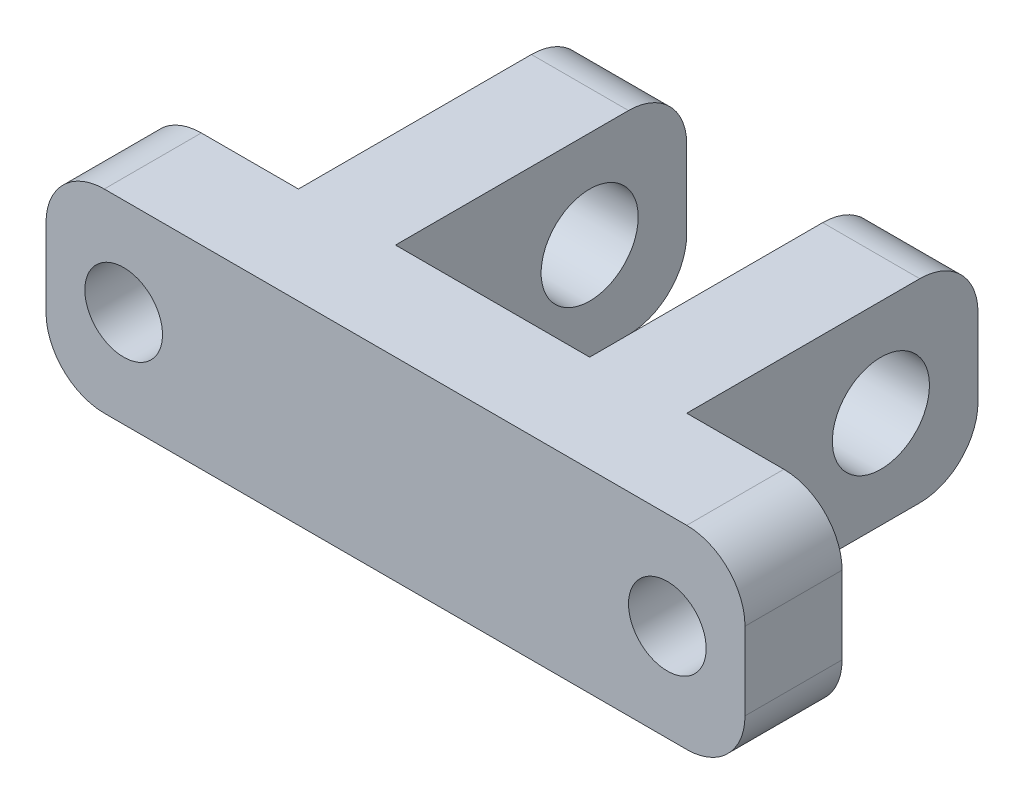
SolidWorks part; units mm, degrees
ref_plane "Front Plane" through (0, 0, 0) normal (0, 0, 1) x (1, 0, 0)
ref_plane "Top Plane" through (0, 0, 0) normal (0, 1, 0) x (1, 0, 0)
ref_plane "Right Plane" through (0, 0, 0) normal (1, 0, 0) x (0, 0, -1)
sketch "Sketch1" plane through (0, 0, 0) normal (0, 1, 0) x (1, 0, 0)
  line L0 (-18, 0) -> (18, 0)
  line L1 (18, 0) -> (18, 5)
  line L2 (18, 5) -> (10, 5)
  line L3 (10, 5) -> (10, 20)
  line L4 (10, 20) -> (5, 20)
  line L5 (5, 20) -> (5, 5)
  line L6 (5, 5) -> (-5, 5)
  line L7 (-5, 5) -> (-5, 20)
  line L8 (-5, 20) -> (-10, 20)
  line L9 (-10, 20) -> (-10, 5)
  line L10 (-10, 5) -> (-18, 5)
  line L11 (-18, 5) -> (-18, 0)
  point P4 (0, 0)
  point P13 (0, 5)
  dimension "D1" = 5
  dimension "D2" = 8
  dimension "D3" = 10
  dimension "D4" = 5
  dimension "D5" = 5
  dimension "D6" = 15
extrude "Boss-Extrude1" add sketch "Sketch1" along normal blind 10
sketch "Sketch2" plane through (10, 0, 0) normal (1, 0, 0) x (0, 0, -1)
  line L0 (20, 10) -> (20, 0) construction
  circle A0 centre (15, 5) radius 2.5
  point P5 (20, 5)
  dimension "D1" = 5
  dimension "D2" = 5
extrude "Cut-Extrude1" cut sketch "Sketch2" against normal through all
fillet "Fillet1" radius 3 8 edges at (7.5, 10, -20) (7.5, 0, -20) (-7.5, 0, -20) (-7.5, 10, -20) (-18, 0, -2.5) (-18, 10, -2.5) (18, 10, -2.5) (18, 0, -2.5)
sketch "Sketch3" plane through (0, 0, -5) normal (0, 0, -1) x (-1, 0, 0)
  line L0 (-18, 7) -> (-18, 3) construction
  circle A0 centre (14, 5) radius 2
  circle A1 centre (-14, 5) radius 2
  point P8 (-18, 5)
  dimension "D1" = 28
  dimension "D2" = 4
  dimension "14" = 14
extrude "Cut-Extrude2" cut sketch "Sketch3" against normal through all
